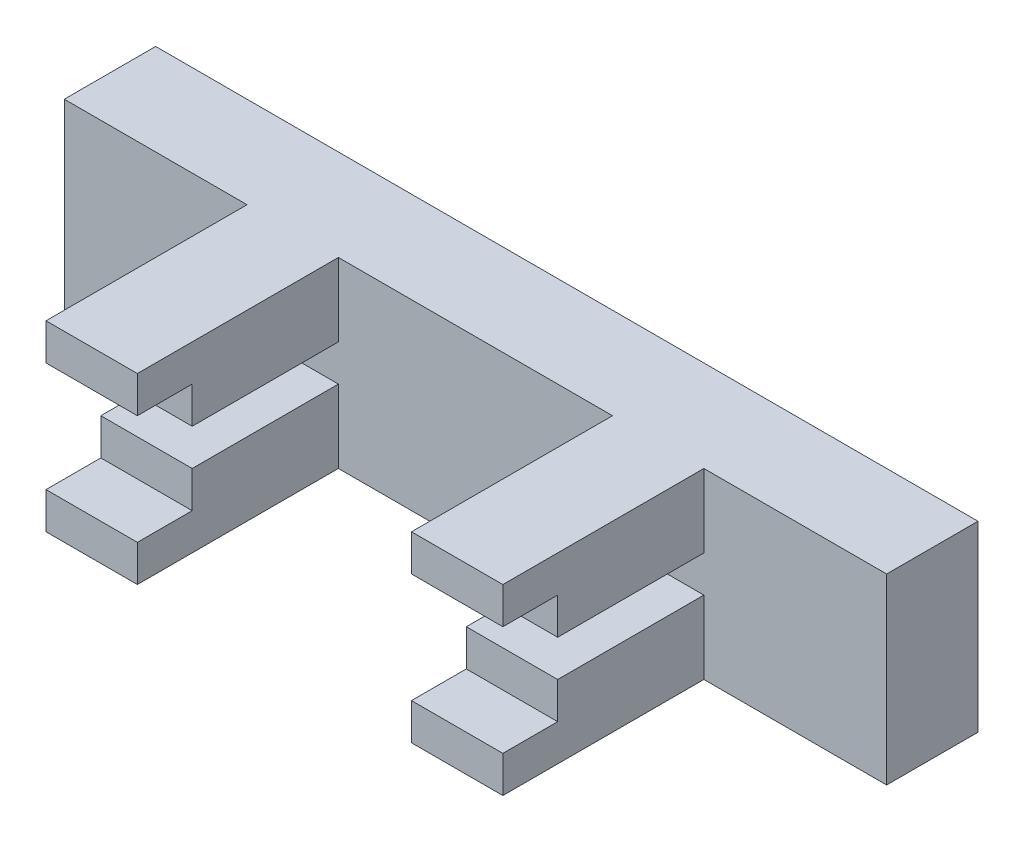
SolidWorks part; units mm, degrees
material "ABS"
ref_plane "Front" through (0, 0, 0) normal (0, 0, 1) x (1, 0, 0)
ref_plane "Top" through (0, 0, 0) normal (0, 1, 0) x (1, 0, 0)
ref_plane "Right" through (0, 0, 0) normal (1, 0, 0) x (0, 0, -1)
sketch "Эскиз1" plane through (0, 0, 0) normal (0, 0, 1) x (1, 0, 0)
  line L1 (-22.5, 5) -> (22.5, 5)
  line L2 (-22.5, 5) -> (-22.5, -5)
  line L3 (-22.5, -5) -> (22.5, -5)
  line L4 (22.5, 5) -> (22.5, -5)
  line L5 (-22.5, 5) -> (22.5, -5) construction
  line L6 (-22.5, -5) -> (22.5, 5) construction
  point P0 (0, 0)
  dimension "D1" = 45
  dimension "D2" = 10
extrude "Бобышка-Вытянуть1" add sketch "Эскиз1" along normal blind 5
sketch "Эскиз2" plane through (0, 0, 5) normal (0, 0, 1) x (1, 0, 0)
  line L1 (22.5, 5) -> (-22.5, 5) construction
  line L2 (-12.5, 5) -> (-7.5, 5)
  line L3 (-12.5, 5) -> (-12.5, 1)
  line L4 (-12.5, 1) -> (-7.5, 1)
  line L5 (-7.5, 5) -> (-7.5, 1)
  line L6 (-22.5, 5) -> (-22.5, -5) construction
  line L7 (22.5, -5) -> (22.5, 5) construction
  line L8 (7.5, 5) -> (12.5, 5)
  line L9 (7.5, 5) -> (7.5, 1)
  line L10 (7.5, 1) -> (12.5, 1)
  line L11 (12.5, 5) -> (12.5, 1)
  dimension "D1" = 4
  dimension "D2" = 5
  dimension "D3" = 10
  dimension "D4" = 5
  dimension "D5" = 4
  dimension "D6" = 10
extrude "Бобышка-Вытянуть2" add sketch "Эскиз2" along normal blind 11
sketch "Эскиз3" plane through (0, 0, 16) normal (0, 0, 1) x (1, 0, 0)
  line L0 (-12.5, 5) -> (-12.5, 1) construction
  line L1 (-12.5, 3) -> (-7.5, 3)
  line L2 (-12.5, 3) -> (-12.5, 1)
  line L3 (-12.5, 1) -> (-7.5, 1)
  line L4 (-7.5, 3) -> (-7.5, 1)
extrude "Вырез-Вытянуть1" cut sketch "Эскиз3" against normal blind 3
sketch "Эскиз4" plane through (0, 0, 16) normal (0, 0, 1) x (1, 0, 0)
  line L0 (7.5, 5) -> (7.5, 1) construction
  line L1 (7.5, 3) -> (12.5, 3)
  line L2 (7.5, 3) -> (7.5, 1)
  line L3 (7.5, 1) -> (12.5, 1)
  line L4 (12.5, 3) -> (12.5, 1)
extrude "Вырез-Вытянуть2" cut sketch "Эскиз4" against normal blind 3
sketch "Эскиз7" plane through (0, 0, 5) normal (0, 0, 1) x (1, 0, 0)
  line L0 (-22.5, -5) -> (22.5, -5) construction
  line L1 (-12.5, -5) -> (-7.5, -5)
  line L2 (-12.5, -5) -> (-12.5, -1)
  line L3 (-12.5, -1) -> (-7.5, -1)
  line L4 (-7.5, -5) -> (-7.5, -1)
  line L5 (-22.5, 5) -> (-22.5, -5) construction
  line L6 (22.5, -5) -> (22.5, 5) construction
  line L7 (7.5, -5) -> (12.5, -5)
  line L8 (7.5, -5) -> (7.5, -1)
  line L9 (7.5, -1) -> (12.5, -1)
  line L10 (12.5, -5) -> (12.5, -1)
  dimension "D1" = 5
  dimension "D2" = 4
  dimension "D3" = 10
  dimension "D4" = 5
  dimension "D5" = 4
  dimension "D6" = 10
extrude "Бобышка-Вытянуть3" add sketch "Эскиз7" along normal blind 11
sketch "Эскиз8" plane through (0, 0, 16) normal (0, 0, 1) x (1, 0, 0)
  line L0 (-7.5, -5) -> (-7.5, -1) construction
  line L1 (-12.5, -1) -> (-7.5, -1)
  line L2 (-12.5, -1) -> (-12.5, -3)
  line L3 (-12.5, -3) -> (-7.5, -3)
  line L4 (-7.5, -1) -> (-7.5, -3)
extrude "Вырез-Вытянуть5" cut sketch "Эскиз8" against normal blind 3
sketch "Эскиз9" plane through (0, 0, 16) normal (0, 0, 1) x (1, 0, 0)
  line L0 (12.5, -5) -> (12.5, -1) construction
  line L1 (7.5, -1) -> (12.5, -1)
  line L2 (7.5, -1) -> (7.5, -3)
  line L3 (7.5, -3) -> (12.5, -3)
  line L4 (12.5, -1) -> (12.5, -3)
extrude "Вырез-Вытянуть6" cut sketch "Эскиз9" against normal blind 3
